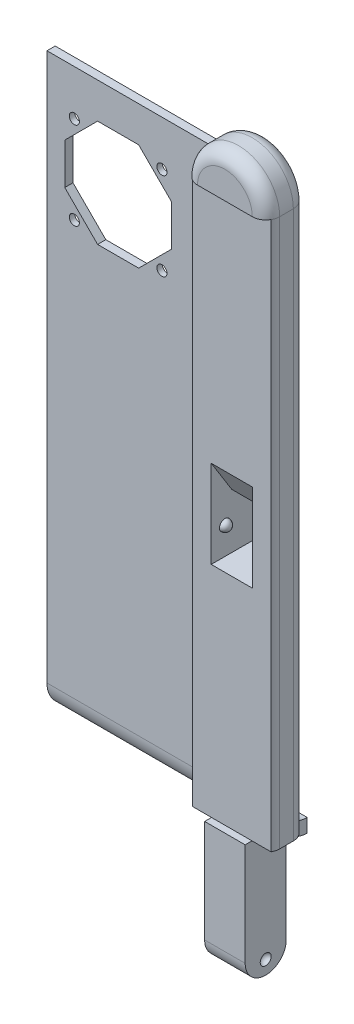
SolidWorks part; units mm, degrees
ref_plane "Front Plane" through (0, 0, 0) normal (0, 0, 1) x (1, 0, 0)
ref_plane "Top Plane" through (0, 0, 0) normal (0, 1, 0) x (1, 0, 0)
ref_plane "Right Plane" through (0, 0, 0) normal (1, 0, 0) x (0, 0, -1)
sketch "Sketch1" plane through (0, 0, 0) normal (0, 0, 1) x (1, 0, 0)
  line L0 (-15, 100) -> (-15, -100)
  line L1 (-15, -100) -> (-7.4, -100)
  line L2 (-7.4, -100) -> (-7.4, -150)
  line L3 (-7.4, -150) -> (7.4, -150)
  line L4 (7.4, -150) -> (7.4, -100)
  line L5 (7.4, -100) -> (15, -100)
  line L6 (15, -100) -> (15, 100)
  arc A0 (15, 100) -> (-15, 100) centre (0, 100) ccw
  dimension "D1" = 15
  dimension "D2" = 250
  dimension "D3" = 50
  dimension "D4" = 15
  dimension "D5" = 14.8
  dimension "D6" = 100
extrude "Boss-Extrude1" add sketch "Sketch1" along normal mid plane 15
fillet "Fillet1" radius 5 6 edges at (-15, 0, -7.5) (0, 115, -7.5) (-15, 0, 7.5) (0, 115, 7.5) (15, 0, -7.5) (15, 0, 7.5)
sketch "Sketch2" plane through (0, 0, 7.5) normal (0, 0, 1) x (1, 0, 0)
  line L0 (-10, 100) -> (-10, -100) construction
  line L1 (-7.5, 0) -> (7.5, 0)
  line L2 (-7.5, 0) -> (-7.5, -20)
  line L3 (-7.5, -20) -> (7.5, -20)
  line L4 (7.5, 0) -> (7.5, -20)
  dimension "D1" = 20
  dimension "D2" = 15
  dimension "D3" = 2.5
extrude "Cut-Extrude1" cut sketch "Sketch2" against normal through all
sketch "Sketch5" plane through (0, 0, 0) normal (0, 0, 1) x (1, 0, 0)
  line L0 (-35.5803, -140) -> (47.5468, -140) construction
  line L1 (-10, -100) -> (-7.4, -100) construction
  line L2 (-7.4, -140) -> (-5.4, -140)
  line L3 (-7.4, -100) -> (-7.4, -150) construction
  line L4 (-7.4, -138) -> (-7.4, -140)
  line L5 (7.4, -140) -> (5.4, -140)
  line L6 (7.4, -150) -> (7.4, -100) construction
  line L7 (7.4, -138) -> (7.4, -140)
  arc A0 (-5.4, -140) -> (-7.4, -138) centre (-7.4, -140) ccw
  arc A1 (5.4, -140) -> (7.4, -138) centre (7.4, -140) cw
  dimension "D1" = 40
  dimension "D2" = 2
  dimension "D3" = 2
revolve "Cut-Revolve1" cut sketch "Sketch5" angle 360 about L0
fillet "Fillet6" radius 5 2 edges at (-7.4, -150, 0) (7.4, -150, 0)
sketch "Sketch7" plane through (7.4, 0, 0) normal (1, 0, 0) x (0, 0, -1)
  line L0 (-7.5, -145) -> (-7.5, -100) construction
  line L1 (7.5, -145) -> (7.5, -100) construction
  line L2 (-7.5, -145) -> (7.5, -145) construction
  line L3 (-7.5, -137.5) -> (-7.5, -150)
  line L4 (-7.5, -150) -> (7.5, -150)
  line L5 (7.5, -150) -> (7.5, -137.5)
  arc A0 (-7.5, -137.5) -> (7.5, -137.5) centre (0, -137.5) ccw
extrude "Cut-Extrude2" cut sketch "Sketch7" against normal through all
sketch "Sketch9" plane through (0, 0, 0) normal (0, 0, 1) x (1, 0, 0)
  line L0 (-32.2513, -10) -> (37.8356, -10) construction
  line L1 (7.5, 0) -> (-7.5, 0) construction
  line L2 (-7.5, -10) -> (-5.5, -10)
  line L3 (-7.5, 0) -> (-7.5, -20) construction
  line L4 (-7.5, -8) -> (-7.5, -10)
  line L5 (7.5, -10) -> (5.5, -10)
  line L6 (7.5, -20) -> (7.5, 0) construction
  line L7 (7.5, -8) -> (7.5, -10)
  arc A0 (-5.5, -10) -> (-7.5, -8) centre (-7.5, -10) ccw
  arc A1 (5.5, -10) -> (7.5, -8) centre (7.5, -10) cw
  dimension "D1" = 10
  dimension "D2" = 2
  dimension "D3" = 2
revolve "Revolve2" add sketch "Sketch9" angle 360 about L0
sketch "Sketch10" plane through (0, 0, 0) normal (1, 0, 0) x (0, 0, -1)
  line L0 (7.5, -100) -> (7.5, 100)
  line L1 (7.5, 100) -> (10.5, 100)
  line L2 (10.5, 100) -> (10.5, -98.5193)
  line L3 (17.5, -105) -> (17.5, -110)
  arc A0 (10.5, -98.5193) -> (17.5, -105) centre (17, -98.5193) ccw
  arc A1 (17.5, -110) -> (7.5, -100) centre (17.5, -100) cw
  dimension "D2" = 10
  dimension "D4" = 6.5
  dimension "D1" = 5
  dimension "D3" = 3
  dimension "D5" = 10
extrude "Boss-Extrude2" add sketch "Sketch10" against normal blind 80
sketch "Sketch11" plane through (0, 0, 0) normal (1, 0, 0) x (0, 0, -1)
  line L0 (17.5, -110) -> (17.5, -105) construction
  line L1 (7.5, 100) -> (7.5, -100) construction
  line L2 (10.5, 100) -> (7.5, 100) construction
  line L3 (10.5, -98.5193) -> (10.5, 100) construction
  line L4 (17.5, -110) -> (17.5, -105)
  line L5 (7.5, 100) -> (7.5, -100)
  line L6 (10.5, 100) -> (7.5, 100)
  line L7 (10.5, -98.5193) -> (10.5, 100)
  arc A0 (10.5, -98.5193) -> (17.5, -105) centre (17, -98.5193) ccw construction
  arc A1 (7.5, -100) -> (17.5, -110) centre (17.5, -100) ccw construction
  arc A2 (10.5, -98.5193) -> (17.5, -105) centre (17, -98.5193) ccw
  arc A3 (7.5, -100) -> (17.5, -110) centre (17.5, -100) ccw
extrude "Boss-Extrude3" add sketch "Sketch11" along normal blind 5
sketch "Sketch12" plane through (0, 0, -10.5) normal (0, 0, -1) x (-1, 0, 0)
  line L0 (7.5, -20) -> (-5, -20) construction
  line L1 (7.5, -20) -> (-5, -20)
  line L2 (7.5, 0) -> (7.5, -20) construction
  line L3 (7.5, 0) -> (-5, 0) construction
  line L4 (80, 100) -> (-5, 100)
  line L5 (-5, 100) -> (-5, -98.5193)
  line L6 (-5, -98.5193) -> (80, -98.5193)
  line L7 (80, -98.5193) -> (80, 100)
  line L9 (-5, 0) -> (-5, -20)
  line L12 (7.5, 0) -> (7.5, -20)
  line L13 (7.5, 0) -> (-5, 0)
  dimension "D1" = 0
extrude "Cut-Extrude3" cut sketch "Sketch12" against normal blind 3
sketch "Sketch13" plane through (-15, 0, 0) normal (-1, 0, 0) x (0, 0, 1)
  line L0 (7.5, -100) -> (5, -100)
  line L1 (2.5, -100) -> (7.5, -100) construction
  line L2 (5, -100) -> (5, 100)
  line L3 (7.5, 100) -> (2.5, 100) construction
  line L4 (5, 100) -> (7.5, 100)
  line L5 (7.5, 100) -> (7.5, -100) construction
  line L6 (7.5, 100) -> (7.5, -100)
extrude "Cut-Extrude4" cut sketch "Sketch13" against normal through all
sketch "Sketch14" plane through (0, 0, -10.5) normal (0, 0, -1) x (-1, 0, 0)
  line L0 (80, -98.5193) -> (-5, -98.5193) construction
  line L1 (80, -98.5193) -> (80, 100) construction
  line L2 (61.5, 86.9807) -> (46.5, 86.9807)
  line L3 (46.5, 86.9807) -> (34.5, 74.9807)
  line L4 (34.5, 74.9807) -> (34.5, 59.9807)
  line L5 (34.5, 59.9807) -> (46.5, 47.9807)
  line L6 (46.5, 47.9807) -> (61.5, 47.9807)
  line L7 (61.5, 47.9807) -> (73.5, 59.9807)
  line L8 (73.5, 59.9807) -> (73.5, 74.9807)
  line L9 (73.5, 74.9807) -> (61.5, 86.9807)
  circle A0 centre (70, 51.4807) radius 1.85
  circle A1 centre (70, 83.4807) radius 1.85
  circle A2 centre (38, 83.4807) radius 1.85
  circle A3 centre (38, 51.4807) radius 1.85
  point P8 (54, 86.9807)
  point P21 (34.5, 67.4807)
  dimension "D4" = 3.7
  dimension "D1" = 150
  dimension "D2" = 32
  dimension "D3" = 32
  dimension "D5" = 10
  dimension "D6" = 15
  dimension "D7" = 16
  dimension "D8" = 16
  dimension "D9" = 39
extrude "Cut-Extrude5" cut sketch "Sketch14" against normal blind 10
sketch "Sketch15" plane through (0, 0, -10.5) normal (0, 0, -1) x (-1, 0, 0)
  circle A0 centre (70, 83.4807) radius 3.25
  circle A1 centre (38, 83.4807) radius 3.25
  circle A2 centre (38, 51.4807) radius 3.25
  circle A3 centre (70, 51.4807) radius 3.25
  dimension "D1" = 6.5
extrude "Cut-Extrude6" cut sketch "Sketch15" against normal blind 1
sketch "Sketch16" plane through (0, 0, 0) normal (1, 0, 0) x (0, 0, -1)
  line L0 (2.5, 0) -> (-5, 12)
  line L1 (2.5, 100) -> (2.5, -100) construction
  line L2 (-5, 100) -> (-5, -100) construction
  line L3 (-5, 12) -> (-5, 0)
  line L4 (-5, 0) -> (2.5, 0)
  point P6 (-5, 9.3271)
  dimension "D1" = 12
extrude "Cut-Extrude7" cut sketch "Sketch16" against normal mid plane 15
